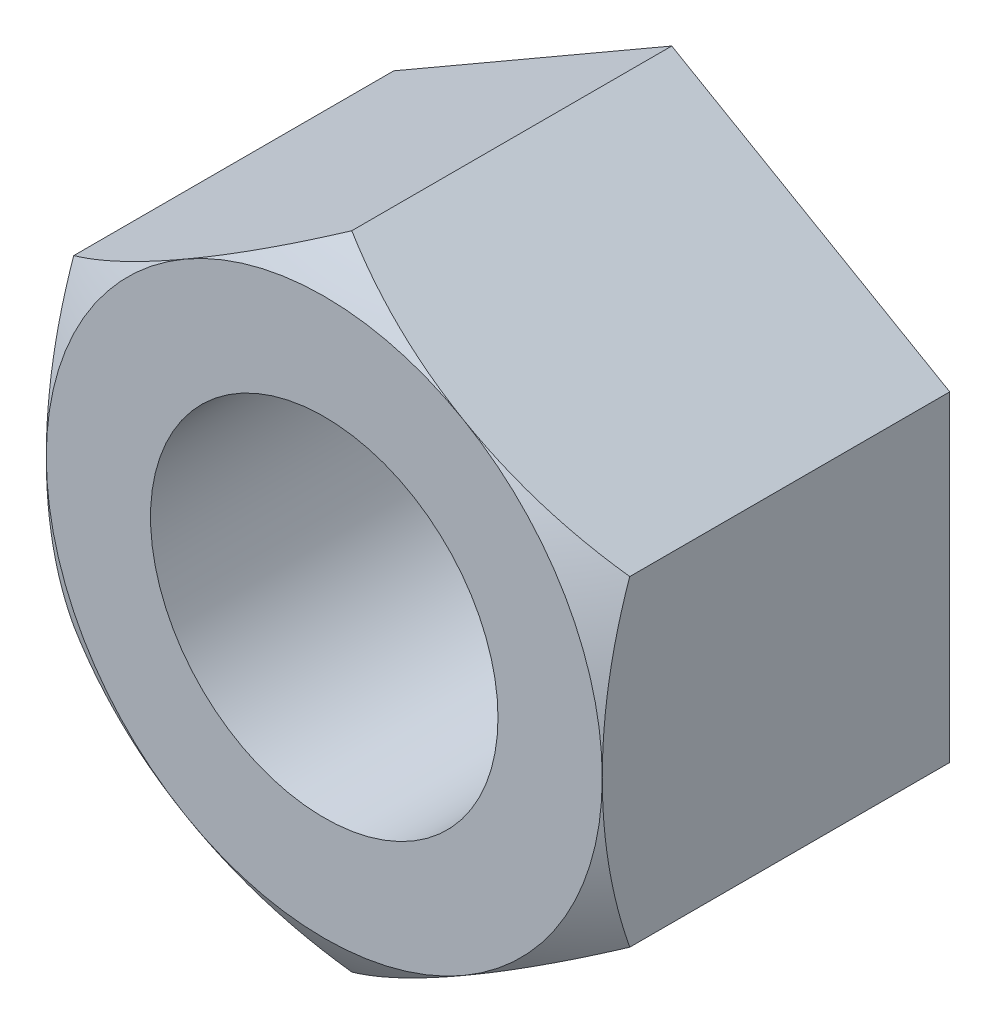
SolidWorks part; units mm, degrees
material "炭素鋼(普通)"
ref_plane "正面" through (0, 0, 0) normal (0, 0, 1) x (1, 0, 0)
ref_plane "平面" through (0, 0, 0) normal (0, 1, 0) x (1, 0, 0)
ref_plane "右側面" through (0, 0, 0) normal (1, 0, 0) x (0, 0, -1)
sketch "ｽｹｯﾁ1" plane through (0, 0, 0) normal (0, 0, 1) x (1, 0, 0)
  line L1 (0, 4.6188) -> (-4, 2.3094)
  line L2 (-4, 2.3094) -> (-4, -2.3094)
  line L3 (-4, -2.3094) -> (0, -4.6188)
  line L4 (0, -4.6188) -> (4, -2.3094)
  line L5 (4, -2.3094) -> (4, 2.3094)
  line L6 (4, 2.3094) -> (0, 4.6188)
  circle A0 centre (0, 0) radius 4 construction
  circle A1 centre (0, 0) radius 2.5
  dimension "D2" = 5
  dimension "D1" = 8
extrude "ﾎﾞｽ - 押し出し1" add sketch "ｽｹｯﾁ1" along normal blind 5
sketch "ｽｹｯﾁ4" plane through (0, 0, 5) normal (0, 0, 1) x (1, 0, 0)
  line L0 (0, 4.6188) -> (-4, 2.3094) construction
  circle A0 centre (0, 0) radius 4
sketch "ｽｹｯﾁ5" plane through (0, 0, 0) normal (1, 0, 0) x (0, 0, -1)
  line L0 (-5, 4) -> (-5, -4) construction
  line L1 (-5, 2.3094) -> (-5, 4.6188) construction
  line L2 (-5, 4.6188) -> (0, 4.6188) construction
  line L3 (0, 0) -> (-5, 0) construction
  line L4 (0, -2.3094) -> (0, 2.3094) construction
  line L5 (-4.6038, 4.6188) -> (-5, 4.6188)
  line L6 (-5, 4.6188) -> (-5, 4)
  line L7 (-5, 4) -> (-4.6427, 4.6188) construction
  arc A0 (-5, 4) -> (-4.6038, 4.6188) centre (1.9282, 0) cw
  dimension "D1" = 30
revolve "ｶｯﾄ - 回転2" cut sketch "ｽｹｯﾁ5" angle 360 about L3
